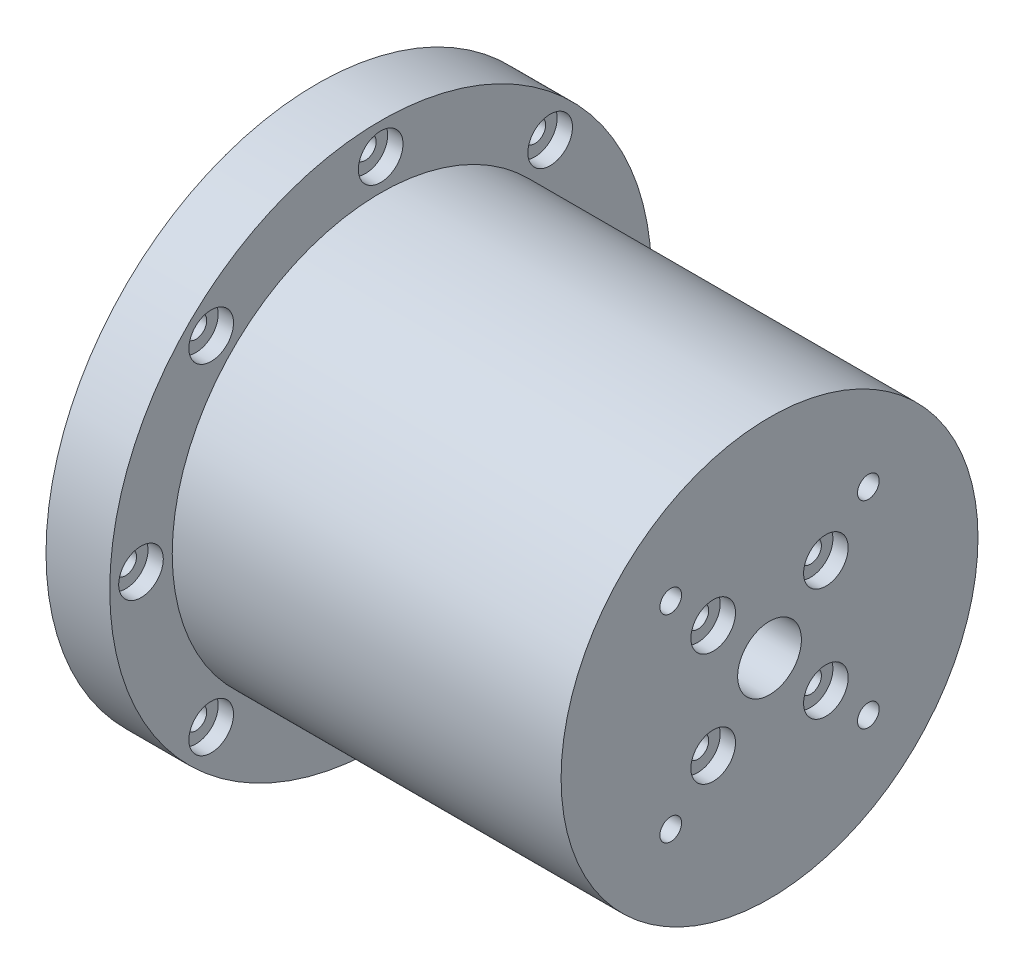
SolidWorks part; units mm, degrees
material "6063-T5"
ref_plane "Front" through (0, 0, 0) normal (0, 0, 1) x (1, 0, 0)
ref_plane "Top" through (0, 0, 0) normal (0, 1, 0) x (1, 0, 0)
ref_plane "Right" through (0, 0, 0) normal (1, 0, 0) x (0, 0, -1)
sketch "Croquis1" plane through (0, 0, 0) normal (1, 0, 0) x (0, 0, -1)
  circle A0 centre (0, 0) radius 32.7
  circle A1 centre (0, 0) radius 5
  dimension "D1" = 65.4
  dimension "D2" = 10
extrude "Saliente-Extruir1" add sketch "Croquis1" along normal mid plane 8.5
hole_wizard "Refrentado para tornillo con cabeza troncocónica de M31" positions "Croquis2" profile "Croquis4" counterbore size "M3" standard "Ansi Metric" end condition up to next
sketch "Croquis2" plane through (4.25, 0, 0) normal (1, 0, 0) x (0, 0, -1)
  line L1 (-8.8388, -8.8388) -> (8.8388, -8.8388) construction
  line L2 (-8.8388, -8.8388) -> (-8.8388, 8.8388) construction
  line L3 (-8.8388, 8.8388) -> (8.8388, 8.8388) construction
  line L4 (8.8388, -8.8388) -> (8.8388, 8.8388) construction
  line L5 (-8.8388, -8.8388) -> (8.8388, 8.8388) construction
  line L6 (-8.8388, 8.8388) -> (8.8388, -8.8388) construction
  point P2 (8.8388, 8.8388)
  point P25 (-8.8388, -8.8388)
  point P26 (-8.8388, 8.8388)
  point P27 (8.8388, -8.8388)
  dimension "D1" = 25
sketch "Croquis4" plane through (4.25, 8.8388, -8.8388) normal (0, 1, 0) x (0, 0, -1)
  line L0 (0, 0) -> (0, 8.5)
  line L1 (0, 8.5) -> (1.7, 8.5)
  line L3 (1.7, 8.5) -> (1.7, 2.4)
  line L4 (1.7, 2.4) -> (3.5, 2.4)
  line L5 (3.5, 2.4) -> (3.5, 0)
  line L7 (3.5, 0) -> (0, 0)
  line L11 (0, -6.35) -> (0, 107.95) construction
  dimension "Diámetro de taladro hasta el siguiente" = 3.4
  dimension "Profundidad de taladro hasta el siguiente" = 8.5
  dimension "Diámetro de refrentado" = 7
  dimension "Profundidad de refrentado" = 2.4
sketch "Croquis5" plane through (-4.25, 0, 0) normal (-1, 0, 0) x (0, 0, 1)
  circle A0 centre (0, 0) radius 21.5
  circle A1 centre (0, 0) radius 32.7 construction
  circle A2 centre (0, 0) radius 32.7
  dimension "D1" = 43
extrude "Saliente-Extruir2" add sketch "Croquis5" along normal blind 55
hole_wizard "Taladro de margen para M31" positions "Croquis6" profile "Croquis8" hole size "M3" standard "Ansi Metric"
sketch "Croquis6" plane through (-59.25, 0, 0) normal (-1, 0, 0) x (0, 0, 1)
  line L1 (-17.075, -17.075) -> (17.075, -17.075) construction
  line L2 (-17.075, -17.075) -> (-17.075, 17.075) construction
  line L3 (-17.075, 17.075) -> (17.075, 17.075) construction
  line L4 (17.075, -17.075) -> (17.075, 17.075) construction
  line L5 (-17.075, -17.075) -> (17.075, 17.075) construction
  line L6 (-17.075, 17.075) -> (17.075, -17.075) construction
  point P2 (17.075, 17.075)
  point P25 (-17.075, -17.075)
  point P26 (-17.075, 17.075)
  point P27 (17.075, -17.075)
  dimension "D1" = 34.15
sketch "Croquis8" plane through (-59.25, 17.075, 17.075) normal (0, 1, 0) x (0, 0, 1)
  line L0 (0, 0) -> (0, 16.0215)
  line L1 (0, 16.0215) -> (1.7, 15)
  line L2 (1.7, 15) -> (1.7, 0)
  line L5 (1.7, 0) -> (0, 0)
  line L10 (0, 16.0215) -> (-1.7, 15) construction
  line L11 (0, -6.35) -> (0, 107.95) construction
  dimension "Diámetro de taladro" = 3.4
  dimension "Profundidad de taladro" = 15
  dimension "Ángulo de perforador" = 118
hole_wizard "Taladro de margen para M32" positions "Croquis9" profile "Croquis10" hole size "M3" standard "Ansi Metric"
sketch "Croquis9" plane through (4.25, 0, 0) normal (1, 0, 0) x (0, 0, -1)
  line L1 (-15.5, -15.5) -> (15.5, -15.5) construction
  line L2 (-15.5, -15.5) -> (-15.5, 15.5) construction
  line L3 (-15.5, 15.5) -> (15.5, 15.5) construction
  line L4 (15.5, -15.5) -> (15.5, 15.5) construction
  line L5 (-15.5, -15.5) -> (15.5, 15.5) construction
  line L6 (-15.5, 15.5) -> (15.5, -15.5) construction
  point P2 (15.5, 15.5)
  point P13 (-15.5, -15.5)
  point P14 (-15.5, 15.5)
  point P15 (15.5, -15.5)
  dimension "D1" = 31
sketch "Croquis10" plane through (4.25, 15.5, -15.5) normal (0, 1, 0) x (0, 0, -1)
  line L0 (0, 0) -> (0, 17.5215)
  line L1 (0, 17.5215) -> (1.7, 16.5)
  line L2 (1.7, 16.5) -> (1.7, 0)
  line L5 (1.7, 0) -> (0, 0)
  line L10 (0, 17.5215) -> (-1.7, 16.5) construction
  line L11 (0, -6.35) -> (0, 107.95) construction
  dimension "Diámetro de taladro" = 3.4
  dimension "Profundidad de taladro" = 16.5
  dimension "Ángulo de perforador" = 118
sketch "Croquis16" plane through (-59.25, 0, 0) normal (-1, 0, 0) x (0, 0, 1)
  line L1 (-21.5, -21.5) -> (21.5, -21.5) construction
  line L2 (-21.5, -21.5) -> (-21.5, 21.5) construction
  line L3 (-21.5, 21.5) -> (21.5, 21.5) construction
  line L4 (21.5, -21.5) -> (21.5, 21.5) construction
  line L5 (-21.5, -21.5) -> (21.5, 21.5) construction
  line L6 (-21.5, 21.5) -> (21.5, -21.5) construction
  line L15 (-16.5, 21.5) -> (16.5, 21.5)
  line L16 (-21.5, 16.5) -> (-21.5, -16.5)
  line L17 (-16.5, -21.5) -> (16.5, -21.5)
  line L18 (21.5, 16.5) -> (21.5, -16.5)
  circle A0 centre (0, 0) radius 21.5 construction
  circle A1 centre (0, 0) radius 32.7
  circle A2 centre (0, 0) radius 32.7
  arc A3 (-21.5, -16.5) -> (-16.5, -21.5) centre (-16.5, -16.5) ccw
  arc A4 (16.5, -21.5) -> (21.5, -16.5) centre (16.5, -16.5) ccw
  arc A5 (16.5, 21.5) -> (21.5, 16.5) centre (16.5, 16.5) cw
  arc A6 (-16.5, 21.5) -> (-21.5, 16.5) centre (-16.5, 16.5) ccw
  dimension "D2" = 5
  dimension "D1" = 0
extrude "Saliente-Extruir3" add sketch "Croquis16" along normal blind 7.5
sketch "Croquis17" plane through (-66.75, 0, 0) normal (-1, 0, 0) x (0, 0, 1)
  circle A0 centre (0, 0) radius 42.5
  circle A1 centre (0, 0) radius 32.7 construction
  circle A2 centre (0, 0) radius 32.7
  dimension "D1" = 85
extrude "Saliente-Extruir4" add sketch "Croquis17" against normal blind 10
hole_wizard "Refrentado para tornillo con cabeza troncocónica de M32" positions "Croquis18" profile "Croquis19" counterbore size "M3" standard "Ansi Metric" end condition up to next
sketch "Croquis18" plane through (-56.75, 0, 0) normal (1, 0, 0) x (0, 0, -1)
  line L0 (0, 39.05) -> (0, -39.05) construction
  line L1 (0, 42.5) -> (0, 32.7) construction
  circle A0 centre (0, 0) radius 42.5 construction
  circle A1 centre (0, 0) radius 32.7 construction
  point P0 (0, 37.6)
  point P15 (0, 37.6)
  point P20 (26.5872, 26.5872)
  point P21 (37.6, 0)
  point P22 (26.5872, -26.5872)
  point P23 (0, -37.6)
  point P24 (-26.5872, -26.5872)
  point P25 (-37.6, 0)
  point P26 (-26.5872, 26.5872)
  dimension "D1" = 8
sketch "Croquis19" plane through (-56.75, 37.6, 0) normal (0, 1, 0) x (0, 0, -1)
  line L0 (0, 0) -> (0, 10)
  line L1 (0, 10) -> (1.7, 10)
  line L3 (1.7, 10) -> (1.7, 2.4)
  line L4 (1.7, 2.4) -> (3.5, 2.4)
  line L5 (3.5, 2.4) -> (3.5, 0)
  line L7 (3.5, 0) -> (0, 0)
  line L11 (0, -6.35) -> (0, 107.95) construction
  dimension "Diámetro de taladro hasta el siguiente" = 3.4
  dimension "Profundidad de taladro hasta el siguiente" = 10
  dimension "Diámetro de refrentado" = 7
  dimension "Profundidad de refrentado" = 2.4
